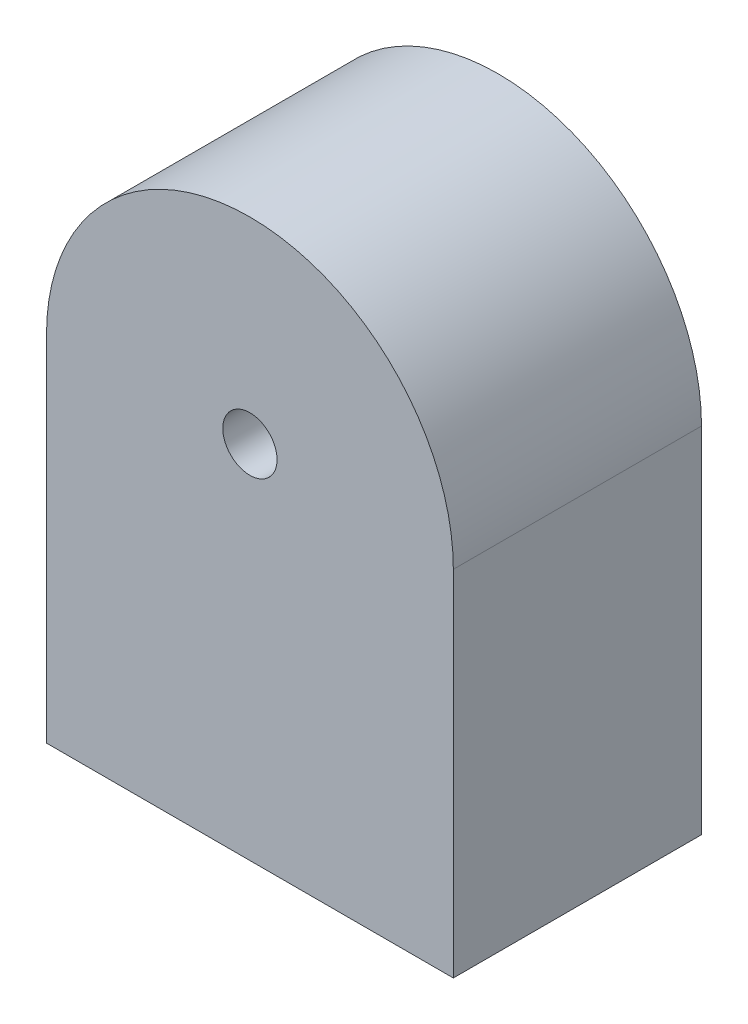
SolidWorks part; units mm, degrees
ref_plane "Plan de face" through (0, 0, 0) normal (0, 0, 1) x (1, 0, 0)
ref_plane "Plan de dessus" through (0, 0, 0) normal (0, 1, 0) x (1, 0, 0)
ref_plane "Plan de droite" through (0, 0, 0) normal (1, 0, 0) x (0, 0, -1)
sketch "Esquisse1" plane through (0, 0, 0) normal (0, 0, 1) x (1, 0, 0)
  line L1 (0, 0) -> (30, 0)
  line L2 (0, 0) -> (0, 26.1)
  line L4 (30, 0) -> (30, 26.1)
  arc A0 (0, 26.1) -> (30, 26.1) centre (15, 26.1) cw
  dimension "D1" = 30
  dimension "D2" = 26.1
extrude "Extrusion1" add sketch "Esquisse1" against normal blind 18.3
sketch "Esquisse2" plane through (0, 0, 0) normal (0, 0, 1) x (1, 0, 0)
  line L0 (0, 26.1) -> (0, 0) construction
  line L1 (0, 0) -> (30, 0) construction
  circle A0 centre (15, 26.6) radius 2
  dimension "D1" = 4
  dimension "D2" = 15
  dimension "D3" = 26.6
extrude "Extrusion2" cut sketch "Esquisse2" against normal blind 6.3
